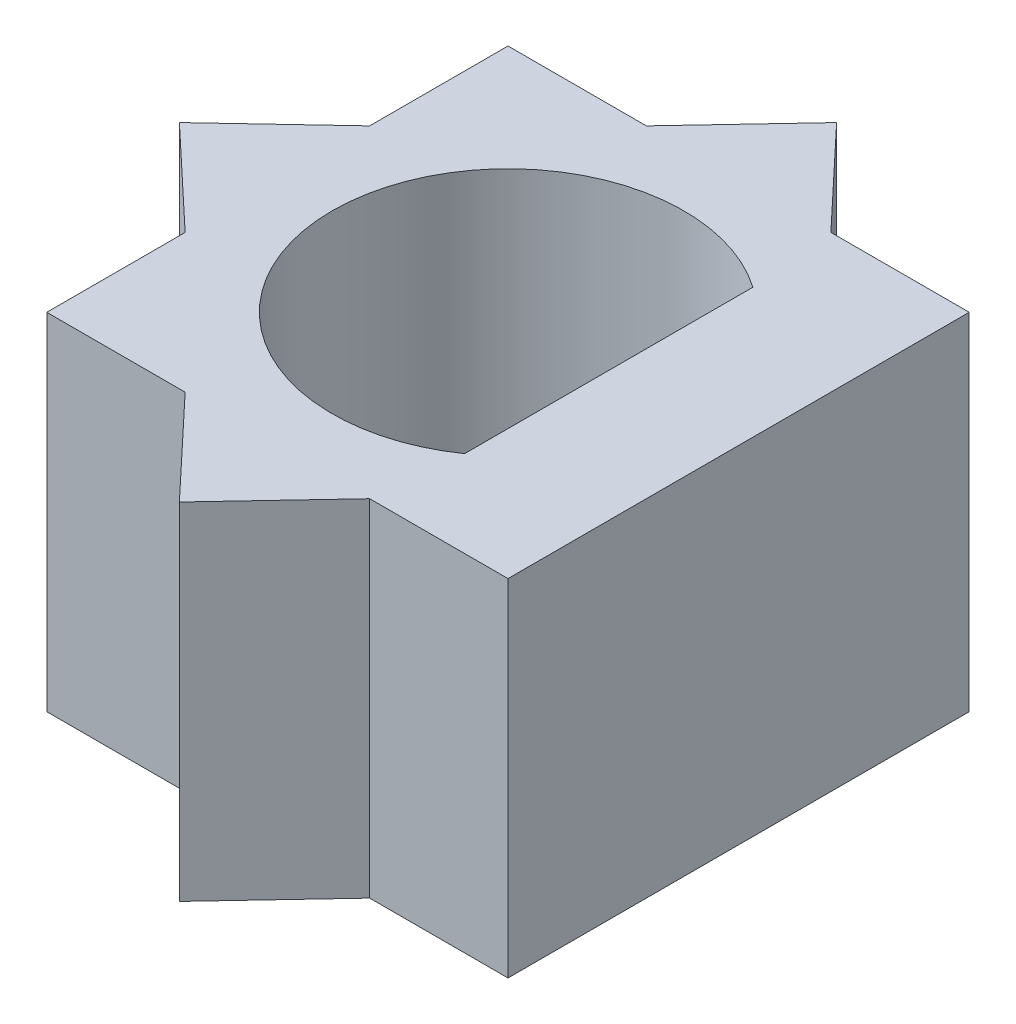
SolidWorks part; units mm, degrees
ref_plane "Plan de face" through (0, 0, 0) normal (0, 0, 1) x (1, 0, 0)
ref_plane "Plan de dessus" through (0, 0, 0) normal (0, 1, 0) x (1, 0, 0)
ref_plane "Plan de droite" through (0, 0, 0) normal (1, 0, 0) x (0, 0, -1)
sketch "Esquisse1" plane through (0, 0, 0) normal (0, 1, 0) x (1, 0, 0)
  line L0 (0, 0) -> (0, 8.5137) construction
  line L1 (-6.9598, 0) -> (8.435, 0) construction
  line L2 (1.1073, -1.1073) -> (9.4238, -9.4238) construction
  line L3 (1.1073, 1.1073) -> (-6.8521, -6.8521) construction
  line L4 (-4, 4) -> (4, 4)
  line L5 (-4, 4) -> (-4, -4)
  line L6 (4, 4) -> (4, -4)
  line L7 (-4, -4) -> (4, -4)
  line L8 (0, 5.7) -> (-1.6, 4)
  line L9 (0, 5.7) -> (1.6, 4)
  line L10 (-5.7, 0) -> (-4, 1.6)
  line L11 (-5.7, 0) -> (-4, -1.6)
  line L12 (0, -5.7) -> (-1.6, -4)
  line L13 (0, -5.7) -> (1.6, -4)
  line L16 (1.7471, 2.5) -> (1.7471, -2.5)
  circle A0 centre (0, 0) radius 3.05
  dimension "D1" = 45
  dimension "5.8" = 6.1
  dimension "D2" = 45
  dimension "D3" = 1.7
  dimension "D4" = 1.7
  dimension "D5" = 2.4
  dimension "D6" = 2.4
  dimension "D7" = 1.7
  dimension "D8" = 2.2529
  dimension "D9" = 2.4
  dimension "D10" = 8
  dimension "D11" = 2.4
  dimension "D12" = 2.4
  dimension "D14" = 2.4
  dimension "D17" = 5
extrude "Boss.-Extru.1" add sketch "Esquisse1" along normal blind 6
